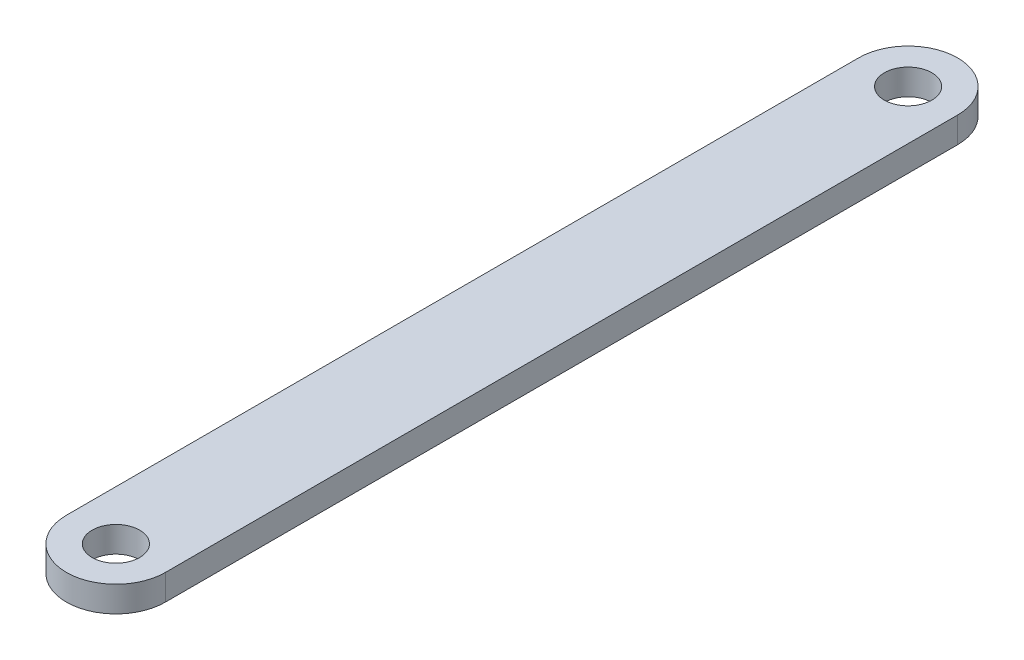
SolidWorks part; units mm, degrees
ref_plane "Front Plane" through (0, 0, 0) normal (0, 0, 1) x (1, 0, 0)
ref_plane "Top Plane" through (0, 0, 0) normal (0, 1, 0) x (1, 0, 0)
ref_plane "Right Plane" through (0, 0, 0) normal (1, 0, 0) x (0, 0, -1)
sketch "Sketch1" plane through (0, 0, 0) normal (0, 1, 0) x (1, 0, 0)
  line L0 (0, 0) -> (0, 200) construction
  line L1 (-12.5, 0) -> (-12.5, 200)
  line L2 (12.5, 0) -> (12.5, 200)
  arc A0 (-12.5, 0) -> (12.5, 0) centre (0, 0) ccw
  arc A1 (12.5, 200) -> (-12.5, 200) centre (0, 200) ccw
  circle A2 centre (0, 200) radius 6
  circle A3 centre (0, 0) radius 6
  point P3 (0, 100)
  dimension "D1" = 12.5
  dimension "D3" = 12
  dimension "D4" = 12
  dimension "D2" = 200
extrude "Boss-Extrude1" add sketch "Sketch1" along normal mid plane 6.5
